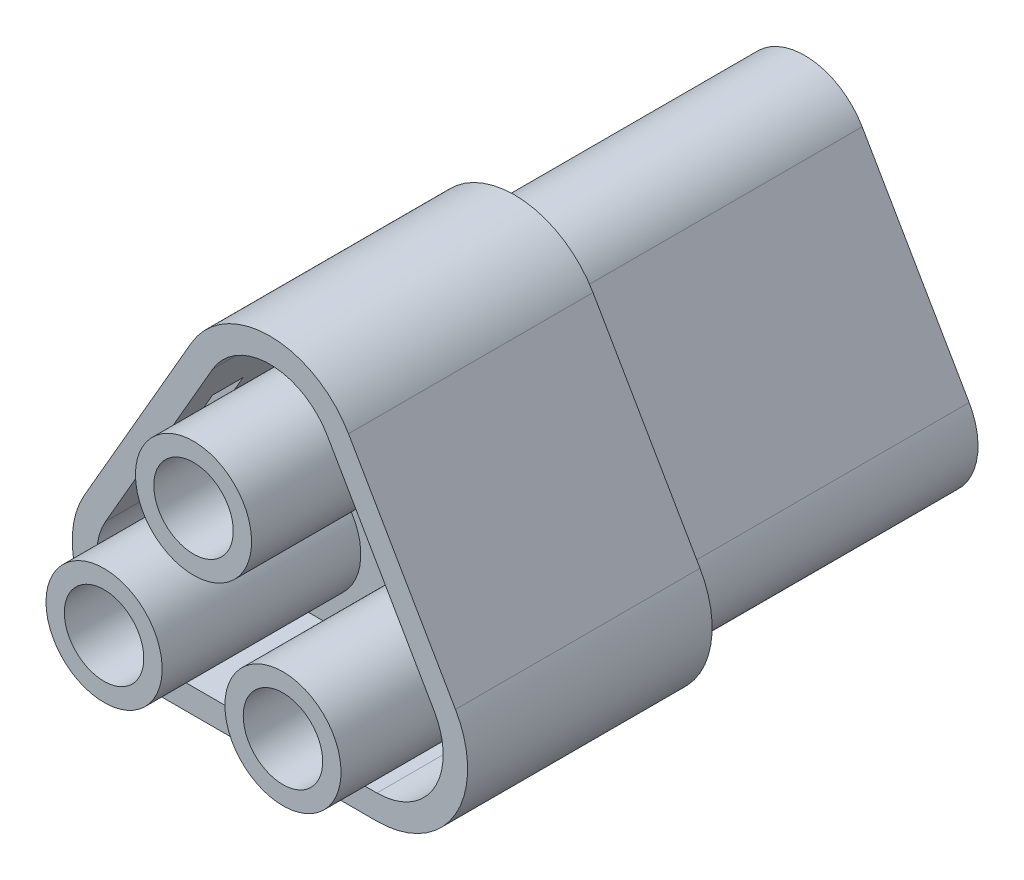
SolidWorks part; units mm, degrees
ref_plane "Спереди" through (0, 0, 0) normal (0, 0, 1) x (1, 0, 0)
ref_plane "Сверху" through (0, 0, 0) normal (0, 1, 0) x (1, 0, 0)
ref_plane "Справа" through (0, 0, 0) normal (1, 0, 0) x (0, 0, -1)
sketch "Эскиз1" plane through (0, 0, 0) normal (0, 0, 1) x (1, 0, 0)
  line L14 (-1.8783, 10.1155) -> (-3.2283, 7.7773)
  line L15 (-3.2283, 7.7773) -> (-2.8819, 7.5773)
  line L16 (-2.6989, 6.8943) -> (-2.9989, 6.3746)
  line L17 (-3.6819, 6.1916) -> (-4.0283, 6.3916)
  line L18 (-4.0283, 6.3916) -> (-5.3783, 4.0534)
  line L19 (-3.5, 0.8) -> (3.5, 0.8)
  line L20 (5.3783, 4.0534) -> (1.8783, 10.1155)
  circle A1 centre (0, 8.3689) radius 1.75 construction
  circle A3 centre (2.9265, 3.3) radius 1.75 construction
  arc A10 (1.8783, 10.1155) -> (-1.8783, 10.1155) centre (0, 9.0311) ccw
  arc A11 (-2.6989, 6.8943) -> (-2.8819, 7.5773) centre (-3.1319, 7.1443) ccw
  arc A12 (-3.6819, 6.1916) -> (-2.9989, 6.3746) centre (-3.4319, 6.6246) ccw
  arc A13 (-5.3783, 4.0534) -> (-3.5, 0.8) centre (-3.5, 2.9689) ccw
  arc A14 (3.5, 0.8) -> (5.3783, 4.0534) centre (3.5, 2.9689) ccw
  circle A15 centre (-2.9265, 3.3) radius 1.75 construction
  circle A16 centre (-2.9265, 3.3) radius 1.9
  circle A17 centre (0, 8.3689) radius 1.9
  circle A18 centre (2.9265, 3.3) radius 1.9
  dimension "D2" = 0.15
extrude "Бобышка-Вытянуть1" add sketch "Эскиз1" along normal blind 9.5
sketch "Эскиз2" plane through (0, 0, 9.5) normal (0, 0, 1) x (1, 0, 0)
  line L0 (6.0712, 4.4534) -> (2.5712, 10.5155) construction
  line L1 (-3.5, 0) -> (3.5, 0) construction
  line L2 (-2.5712, 10.5155) -> (-6.0712, 4.4534) construction
  line L3 (6.0712, 4.4534) -> (2.5712, 10.5155)
  line L4 (-3.5, 0) -> (3.5, 0)
  line L5 (-2.5712, 10.5155) -> (-6.0712, 4.4534)
  arc A1 (2.5712, 10.5155) -> (-2.5712, 10.5155) centre (0, 9.0311) ccw construction
  arc A2 (3.5, 0) -> (6.0712, 4.4534) centre (3.5, 2.9689) ccw construction
  arc A3 (-6.0712, 4.4534) -> (-3.5, 0) centre (-3.5, 2.9689) ccw construction
  arc A4 (2.5712, 10.5155) -> (-2.5712, 10.5155) centre (0, 9.0311) ccw
  arc A5 (3.5, 0) -> (6.0712, 4.4534) centre (3.5, 2.9689) ccw
  arc A6 (-6.0712, 4.4534) -> (-3.5, 0) centre (-3.5, 2.9689) ccw
extrude "Бобышка-Вытянуть2" add sketch "Эскиз2" along normal blind 4
sketch "Эскиз3" plane through (0, 0, 13.5) normal (0, 0, 1) x (1, 0, 0)
  line L0 (-1.8783, 10.1155) -> (-5.3783, 4.0534)
  line L1 (-3.5, 0.8) -> (3.5, 0.8)
  line L2 (5.3783, 4.0534) -> (1.8783, 10.1155)
  line L3 (6.0712, 4.4534) -> (2.5712, 10.5155)
  line L4 (-2.5712, 10.5155) -> (-6.0712, 4.4534)
  line L5 (-3.5, 0) -> (3.5, 0)
  line L6 (6.0712, 4.4534) -> (2.5712, 10.5155) construction
  line L7 (-2.5712, 10.5155) -> (-6.0712, 4.4534) construction
  line L8 (-3.5, 0) -> (3.5, 0) construction
  arc A0 (1.8783, 10.1155) -> (-1.8783, 10.1155) centre (0, 9.0311) ccw
  arc A1 (-5.3783, 4.0534) -> (-3.5, 0.8) centre (-3.5, 2.9689) ccw
  arc A2 (3.5, 0.8) -> (5.3783, 4.0534) centre (3.5, 2.9689) ccw
  arc A3 (3.5, 0) -> (6.0712, 4.4534) centre (3.5, 2.9689) ccw
  arc A4 (2.5712, 10.5155) -> (-2.5712, 10.5155) centre (0, 9.0311) ccw
  arc A5 (-6.0712, 4.4534) -> (-3.5, 0) centre (-3.5, 2.9689) ccw
  arc A6 (3.5, 0) -> (6.0712, 4.4534) centre (3.5, 2.9689) ccw construction
  arc A7 (2.5712, 10.5155) -> (-2.5712, 10.5155) centre (0, 9.0311) ccw construction
  arc A8 (-6.0712, 4.4534) -> (-3.5, 0) centre (-3.5, 2.9689) ccw construction
  arc M7 (3.5, 0) -> (6.0712, 4.4534) centre (3.5, 2.9689) ccw
  line M8 (6.0712, 4.4534) -> (2.5712, 10.5155)
  arc M9 (2.5712, 10.5155) -> (-2.5712, 10.5155) centre (0, 9.0311) ccw
  line M10 (-2.5712, 10.5155) -> (-6.0712, 4.4534)
  arc M11 (-6.0712, 4.4534) -> (-3.5, 0) centre (-3.5, 2.9689) ccw
  line M12 (-3.5, 0) -> (3.5, 0)
  dimension "D1" = 0
  dimension "D2" = 0.8
extrude "Бобышка-Вытянуть3" add sketch "Эскиз3" along normal blind 4 contours A2 L1 A1 L0 A0 L2 M12 M7 M8 M9 M10 M11
sketch "Эскиз4" plane through (0, 0, 9.5) normal (0, 0, -1) x (-1, 0, 0)
  circle A0 centre (0, 8.3689) radius 1.9 construction
  circle A1 centre (-2.9265, 3.3) radius 1.9 construction
  circle A2 centre (2.9265, 3.3) radius 1.9 construction
  circle A3 centre (0, 8.3689) radius 1.9
  circle A4 centre (-2.9265, 3.3) radius 1.9
  circle A5 centre (2.9265, 3.3) radius 1.9
  circle A6 centre (0, 8.3689) radius 1.75
  circle A7 centre (-2.9265, 3.3) radius 1.75
  circle A8 centre (2.9265, 3.3) radius 1.75
  dimension "D1" = 0.15
extrude "Бобышка-Вытянуть4" add sketch "Эскиз4" along normal up to surface (9.5 mm away) separate body up to face at (-1.6116, 5.9201, 0)
sketch "Эскиз5" plane through (0, 0, 13.5) normal (0, 0, 1) x (1, 0, 0)
  circle A0 centre (0, 8.3689) radius 1.9 construction
  circle A1 centre (2.9265, 3.3) radius 1.9 construction
  circle A2 centre (-2.9265, 3.3) radius 1.9 construction
  circle A3 centre (0, 8.3689) radius 1.9
  circle A4 centre (2.9265, 3.3) radius 1.9
  circle A5 centre (-2.9265, 3.3) radius 1.9
  circle A6 centre (0, 8.3689) radius 1.3
  circle A7 centre (-2.9265, 3.3) radius 1.3
  circle A8 centre (2.9265, 3.3) radius 1.3
  dimension "D1" = 0.6
extrude "Бобышка-Вытянуть5" add sketch "Эскиз5" along normal blind 6.5 separate body
sketch "Эскиз6" plane through (-6.4817, 3.7422, 0) normal (-0.866, 0.5, 0) x (0, 0, 1)
  line L0 (17.5, 4.3212) -> (16, 4.3212) construction
  line L1 (17.5, 7.8212) -> (17.5, 0.8212) construction
  line L3 (16.5, 2.8212) -> (15.5, 2.8212)
  line L4 (16.5, 2.8212) -> (16.5, 5.8212)
  line L5 (16.5, 5.8212) -> (15.5, 5.8212)
  line L6 (15.5, 2.8212) -> (15.5, 5.8212)
  line L7 (16.5, 2.8212) -> (15.5, 5.8212) construction
  line L8 (16.5, 5.8212) -> (15.5, 2.8212) construction
  dimension "D1" = 2
  dimension "D2" = 1
  dimension "D3" = 3
extrude "Вырез-Вытянуть1" cut sketch "Эскиз6" against normal blind 1
